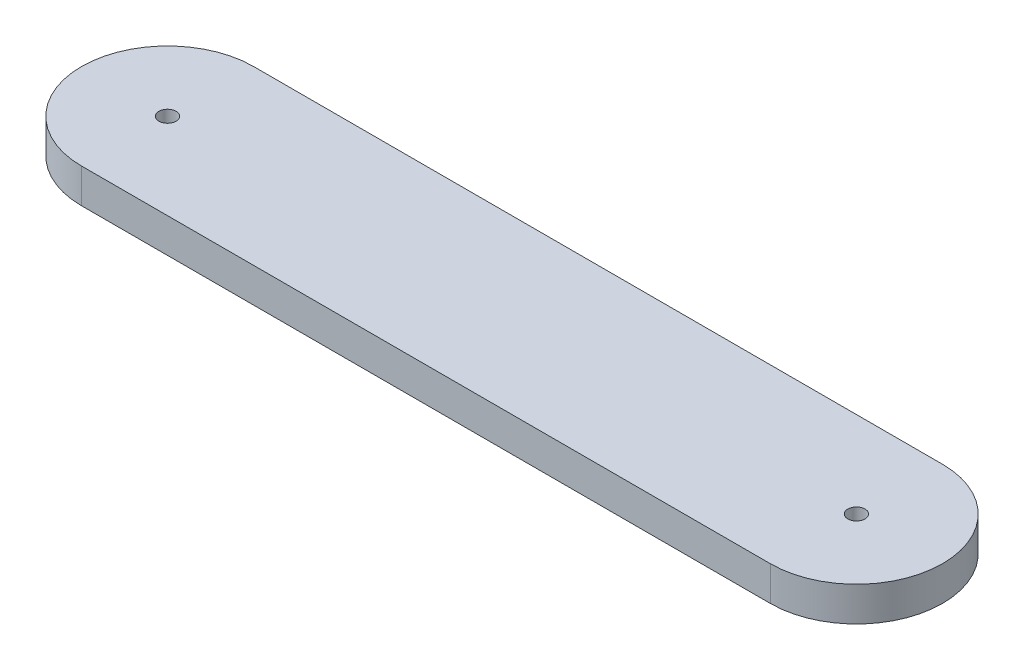
SolidWorks part; units mm, degrees
ref_plane "Front Plane" through (0, 0, 0) normal (0, 0, 1) x (1, 0, 0)
ref_plane "Top Plane" through (0, 0, 0) normal (0, 1, 0) x (1, 0, 0)
ref_plane "Right Plane" through (0, 0, 0) normal (1, 0, 0) x (0, 0, -1)
sketch "Sketch2" plane through (0, 0, 0) normal (0, 1, 0) x (1, 0, 0)
  line L0 (0, 25) -> (200, 25)
  line L1 (0, -25) -> (200, -25)
  arc A1 (0, 25) -> (0, -25) centre (0, 0) ccw
  arc A2 (200, -25) -> (200, 25) centre (200, 0) ccw
  circle A3 centre (0, 0) radius 2.5
  circle A4 centre (200, 0) radius 2.5
  dimension "D1" = 25
  dimension "D2" = 5
  dimension "D3" = 5
  dimension "D5" = 0
  dimension "D6" = 200
  dimension "D7" = 25
extrude "Boss-Extrude2" add sketch "Sketch2" along normal blind 10
